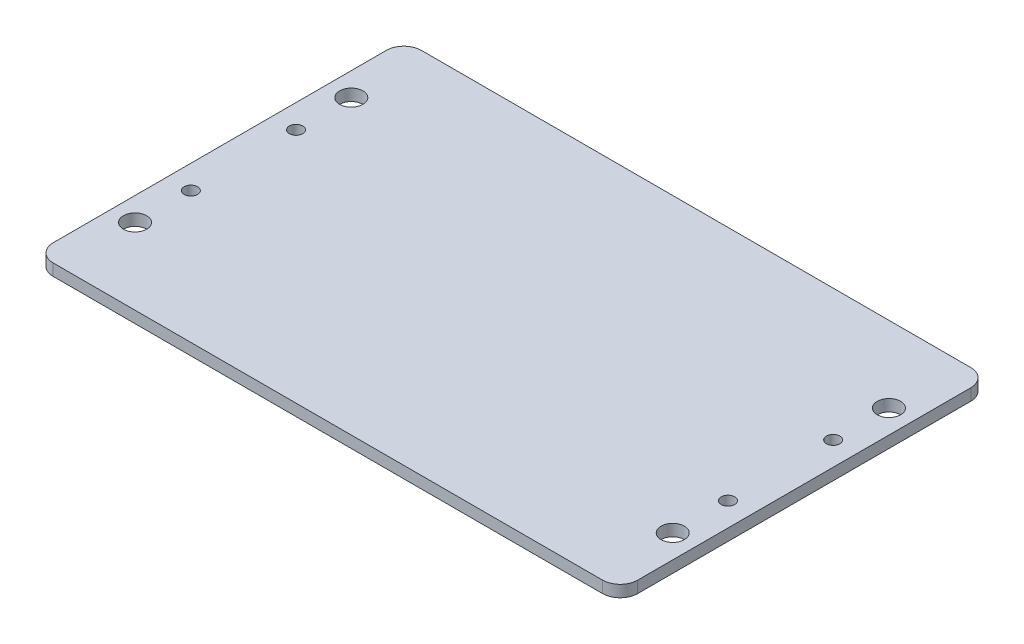
SolidWorks part; units mm, degrees
ref_plane "Plano frontal" through (0, 0, 0) normal (0, 0, 1) x (1, 0, 0)
ref_plane "Plano superior" through (0, 0, 0) normal (0, 1, 0) x (1, 0, 0)
ref_plane "Plano direito" through (0, 0, 0) normal (1, 0, 0) x (0, 0, -1)
sketch "Esboço1" plane through (0, 0, 0) normal (0, 1, 0) x (1, 0, 0)
  line L7 (-50, 31.5) -> (50, 31.5)
  line L8 (50, 31.5) -> (50, -31.5)
  line L9 (50, -31.5) -> (-50, -31.5)
  line L10 (-50, -31.5) -> (-50, 31.5)
  line L11 (0, 31.5) -> (0, -31.5) construction
  line L12 (-50, 0) -> (50, 0) construction
  dimension "D1" = 63
  dimension "D2" = 100
extrude "Ressalto-extrusão1" add sketch "Esboço1" along normal blind 2
sketch "Esboço5" plane through (0, 2, 0) normal (0, 1, 0) x (1, 0, 0)
  line L2 (50, 31.5) -> (-50, 31.5) construction
  line L3 (50, -31.5) -> (50, 31.5) construction
  line L4 (50, 0) -> (-50, 0) construction
  line L5 (-50, 31.5) -> (-50, -31.5) construction
  line L6 (0, 31.5) -> (0, -31.5) construction
  line L7 (-50, -31.5) -> (50, -31.5) construction
  line L8 (53.5484, -13.175) -> (53.5484, -27.5) construction
  line L9 (-53.5484, -13.175) -> (-53.5484, -27.5) construction
  line L10 (-53.5484, 21.175) -> (-53.5484, 35.5) construction
  circle A0 centre (46, 18.5) radius 2
  circle A1 centre (46, -18.5) radius 2
  circle A2 centre (-46, -18.5) radius 2
  circle A3 centre (-46, 18.5) radius 2
  dimension "D2" = 4
  dimension "D1" = 4
  dimension "D3" = 13
extrude "Corte-extrusão3" cut sketch "Esboço5" against normal through all
fillet "Filete1" radius 3 4 edges at (50, 1, -31.5) (50, 1, 31.5) (-50, 1, 31.5) (-50, 1, -31.5)
sketch "Esboço6" plane through (0, 0, 0) normal (0, -1, 0) x (1, 0, 0)
  line L0 (0, 0) -> (0, 31.5) construction
  line L1 (-47, 31.5) -> (47, 31.5) construction
  line L2 (0, 0) -> (-50, 0) construction
  line L3 (-50, -28.5) -> (-50, 28.5) construction
  circle A4 centre (45.95, 9) radius 1.15
  circle A5 centre (45.95, -9) radius 1.15
  circle A6 centre (-45.95, -9) radius 1.15
  circle A7 centre (-45.95, 9) radius 1.15
extrude "Corte-extrusão4" cut sketch "Esboço6" against normal through all
